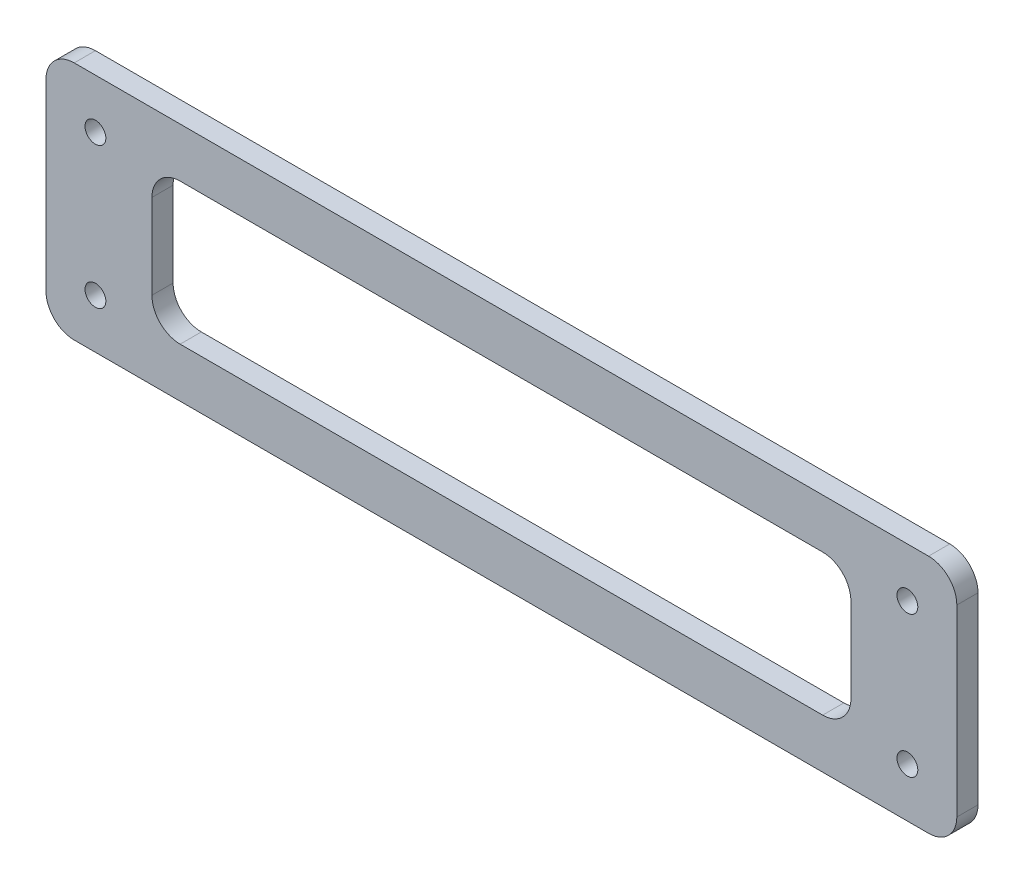
SolidWorks part; units mm, degrees
ref_plane "前视基准面" through (0, 0, 0) normal (0, 0, 1) x (1, 0, 0)
ref_plane "上视基准面" through (0, 0, 0) normal (0, 1, 0) x (1, 0, 0)
ref_plane "右视基准面" through (0, 0, 0) normal (1, 0, 0) x (0, 0, -1)
sketch "草图1" plane through (0, 0, 0) normal (0, 0, 1) x (1, 0, 0)
  line L0 (0, -883.6766) -> (0, 43300.1518) construction
  line L1 (-64.5, -17) -> (64.5, -17)
  line L2 (-64.5, -17) -> (-64.5, 17)
  line L3 (-64.5, 17) -> (64.5, 17)
  line L4 (64.5, -17) -> (64.5, 17)
  line L5 (-64.5, -17) -> (64.5, 17) construction
  line L6 (-64.5, 17) -> (64.5, -17) construction
  line L7 (-57.5, 17) -> (-57.5, -17) construction
  line L9 (-49.5, -10) -> (49.5, -10)
  line L10 (-49.5, -10) -> (-49.5, 10)
  line L11 (-49.5, 10) -> (49.5, 10)
  line L12 (49.5, -10) -> (49.5, 10)
  line L13 (-49.5, -10) -> (49.5, 10) construction
  line L14 (-49.5, 10) -> (49.5, -10) construction
  circle A0 centre (-57.5, 10) radius 1.475
  circle A1 centre (-57.5, -10) radius 1.475
  circle A2 centre (57.5, -10) radius 1.475
  circle A3 centre (57.5, 10) radius 1.475
  point P0 (0, 0)
  point P18 (0, 0)
  dimension "D1" = 20
  dimension "D2" = 10
  dimension "D3" = 2.95
  dimension "D5" = 7
  dimension "D4" = 7
  dimension "D6" = 57.5
  dimension "D7" = 8
  dimension "D8" = 7
extrude "凸台-拉伸1" add sketch "草图1" along normal blind 3
fillet "圆角1" radius 4 8 edges at (49.5, 10, 1.5) (-49.5, 10, 1.5) (-49.5, -10, 1.5) (49.5, -10, 1.5) (64.5, -17, 1.5) (-64.5, -17, 1.5) (64.5, 17, 1.5) (-64.5, 17, 1.5)
